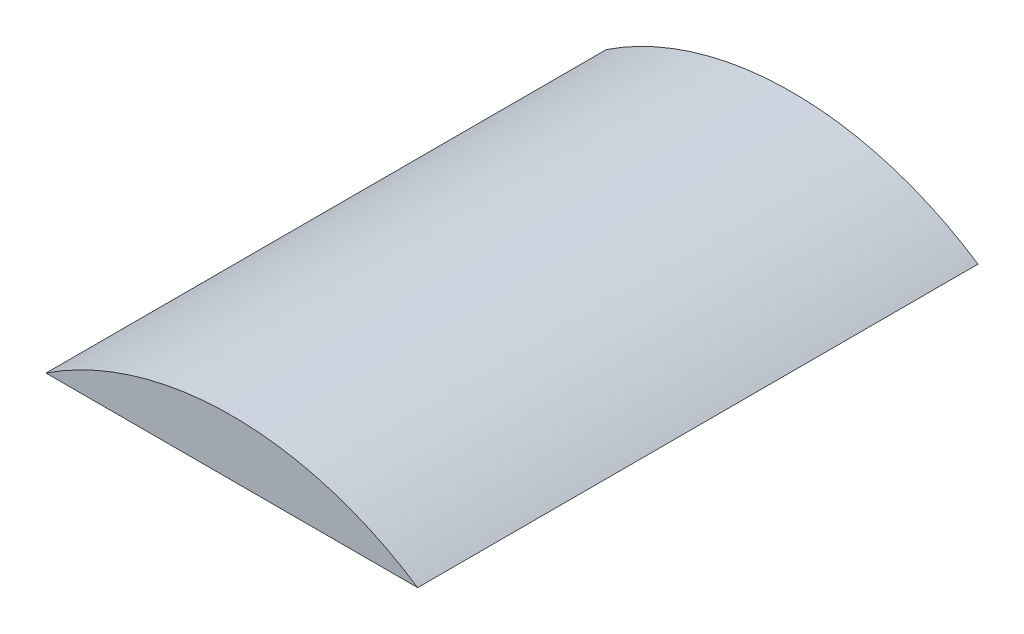
SolidWorks part; units mm, degrees
ref_plane "Front Plane" through (0, 0, 0) normal (0, 0, 1) x (1, 0, 0)
ref_plane "Top Plane" through (0, 0, 0) normal (0, 1, 0) x (1, 0, 0)
ref_plane "Right Plane" through (0, 0, 0) normal (1, 0, 0) x (0, 0, -1)
sketch "Sketch1" plane through (0, 0, 0) normal (0, 0, 1) x (1, 0, 0)
  line L0 (-1.6583, 2.5) -> (1.6583, 2.5)
  arc A0 (1.6583, 2.5) -> (-1.6583, 2.5) centre (0, 0) ccw
  dimension "D1" = 6
  dimension "D2" = 2.5
extrude "Boss-Extrude1" add sketch "Sketch1" along normal blind 5
